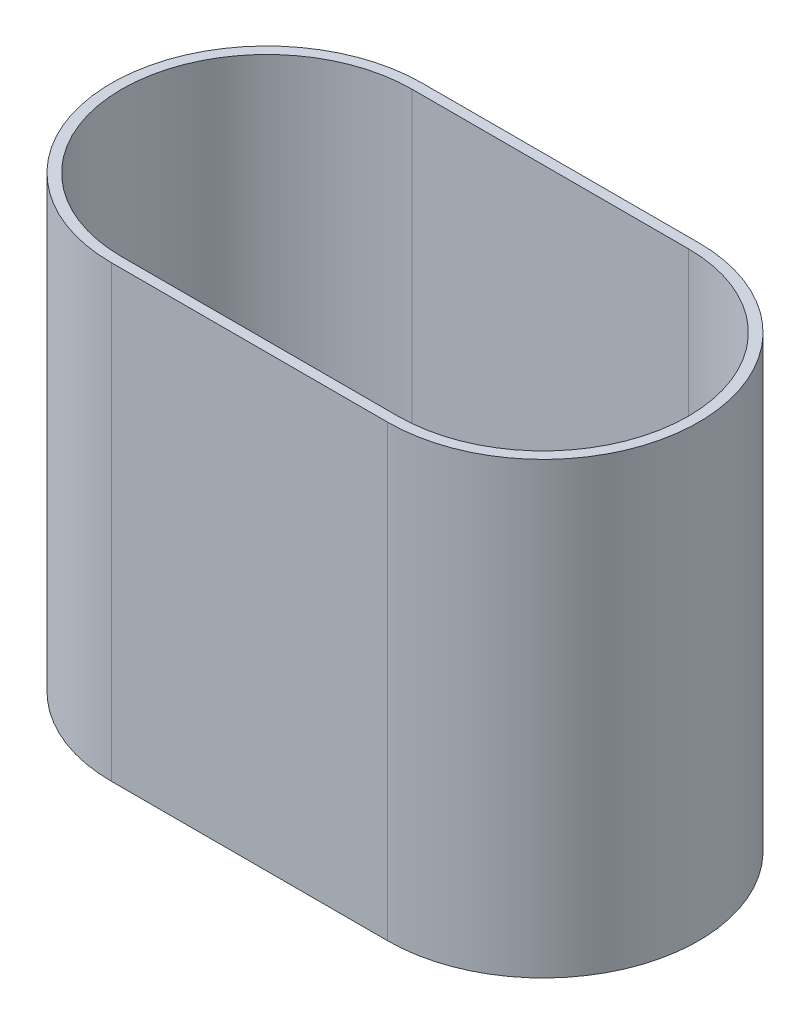
SolidWorks part; units mm, degrees
ref_plane "Front Plane" through (0, 0, 0) normal (0, 0, 1) x (1, 0, 0)
ref_plane "Top Plane" through (0, 0, 0) normal (0, 1, 0) x (1, 0, 0)
ref_plane "Right Plane" through (0, 0, 0) normal (1, 0, 0) x (0, 0, -1)
sketch "Sketch1" plane through (0, 0, 0) normal (0, 1, 0) x (1, 0, 0)
  line L0 (0, 0) -> (85, 0) construction
  line L1 (85, 0) -> (40, 0) construction
  line L3 (-40, -45) -> (40, -45)
  line L4 (-40, 45) -> (40, 45)
  arc A0 (40, -45) -> (40, 45) centre (40, 0) ccw
  arc A1 (-40, -45) -> (-40, 45) centre (-40, 0) cw
  dimension "D1" = 85
  dimension "D2" = 45
extrude "Boss-Extrude1" add sketch "Sketch1" along normal blind 130
shell "Shell1" thickness 3
